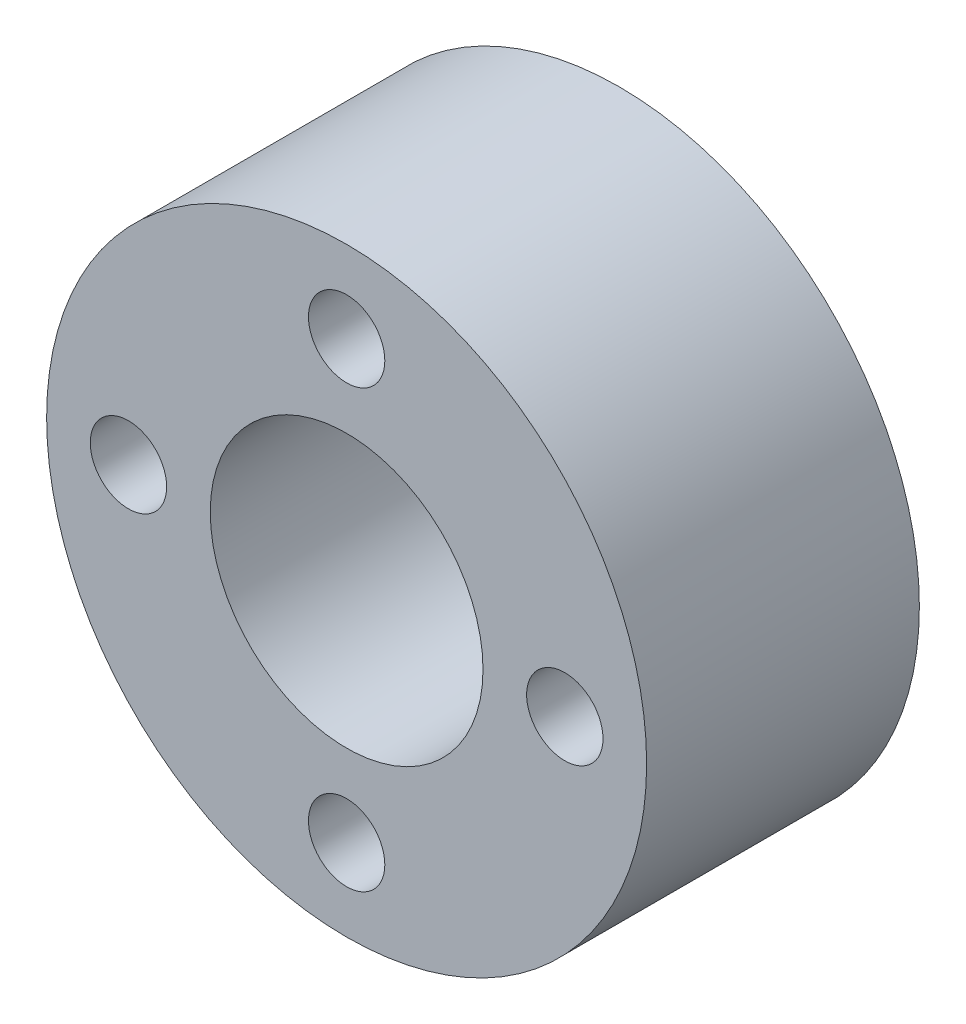
SolidWorks part; units mm, degrees
ref_plane "前视基准面" through (0, 0, 0) normal (0, 0, 1) x (1, 0, 0)
ref_plane "上视基准面" through (0, 0, 0) normal (0, 1, 0) x (1, 0, 0)
ref_plane "右视基准面" through (0, 0, 0) normal (1, 0, 0) x (0, 0, -1)
other "Configuration Table"
sketch "草图1" plane through (0, 0, 0) normal (0, 0, 1) x (1, 0, 0)
  circle A0 centre (0, 0) radius 27.5
extrude "凸台-拉伸1" add sketch "草图1" against normal blind 25
sketch "草图2" plane through (0, 0, 0) normal (0, 0, 1) x (1, 0, 0)
  circle A0 centre (0, 0) radius 12.5
  circle A1 centre (20, 0) radius 3.5
  circle A2 centre (0, 20) radius 3.5
  circle A3 centre (-20, 0) radius 3.5
  circle A4 centre (0, -20) radius 3.5
extrude "切除-拉伸1" cut sketch "草图2" against normal blind 25
